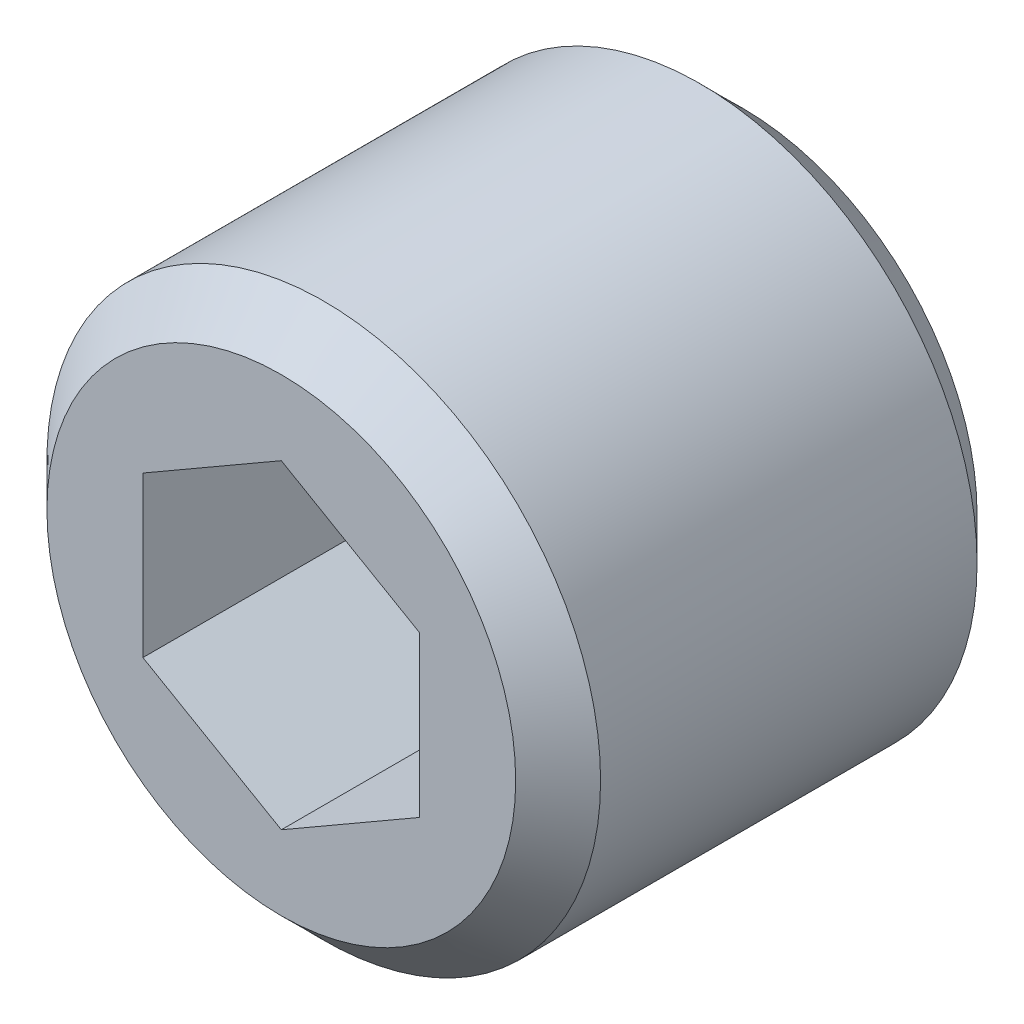
SolidWorks part; units mm, degrees
ref_plane "Płaszczyzna przednia" through (0, 0, 0) normal (0, 0, 1) x (1, 0, 0)
ref_plane "Płaszczyzna górna" through (0, 0, 0) normal (0, 1, 0) x (1, 0, 0)
ref_plane "Płaszczyzna prawa" through (0, 0, 0) normal (1, 0, 0) x (0, 0, -1)
ref_plane "Płaszczyzna1" through (0, 0, 10) normal (0, 0, 1) x (1, 0, 0)
sketch "Szkic1" plane through (0, 0, 0) normal (1, 0, 0) x (0, 0, -1)
  line L0 (-10, 0) -> (-10, 5.08)
  line L1 (-10, 5.08) -> (-9.08, 6)
  line L2 (-9.08, 6) -> (-0.92, 6)
  line L3 (-0.92, 6) -> (0, 5.08)
  line L4 (0, 5.08) -> (0, 0)
  line L5 (0, 0) -> (-10, 0)
  line L6 (0, 0) -> (-10, 0) construction
revolve "Obrót1" add sketch "Szkic1" angle 360 about L6
cosmetic thread "Oznaczenie gwintu1"
sketch "Szkic2" plane through (0, 0, 0) normal (1, 0, 0) x (0, 0, -1)
  line L0 (-10, 0) -> (-10, 3.9641)
  line L1 (-10, 3.9641) -> (-5, 3.9641)
  line L2 (-5, 3.9641) -> (-2.7113, 0)
  line L3 (-2.7113, 0) -> (-10, 0)
  line L4 (-2.7113, 0) -> (-10, 0) construction
revolve "Wycięcie-obrót1" cut sketch "Szkic2" angle 360 about L4
sketch "Szkic3" plane through (0, 0, 10) normal (0, 0, 1) x (1, 0, 0)
  line L0 (-3, 1.7321) -> (-3, -1.7321)
  line L1 (-3, -1.7321) -> (0, -3.4641)
  line L2 (0, -3.4641) -> (3, -1.7321)
  line L3 (3, -1.7321) -> (3, 1.7321)
  line L4 (3, 1.7321) -> (0, 3.4641)
  line L5 (0, 3.4641) -> (-3, 1.7321)
  circle A0 centre (0, 0) radius 4.1641
extrude "Dodanie-wyciągnięcie1" add sketch "Szkic3" against normal blind 7.5
